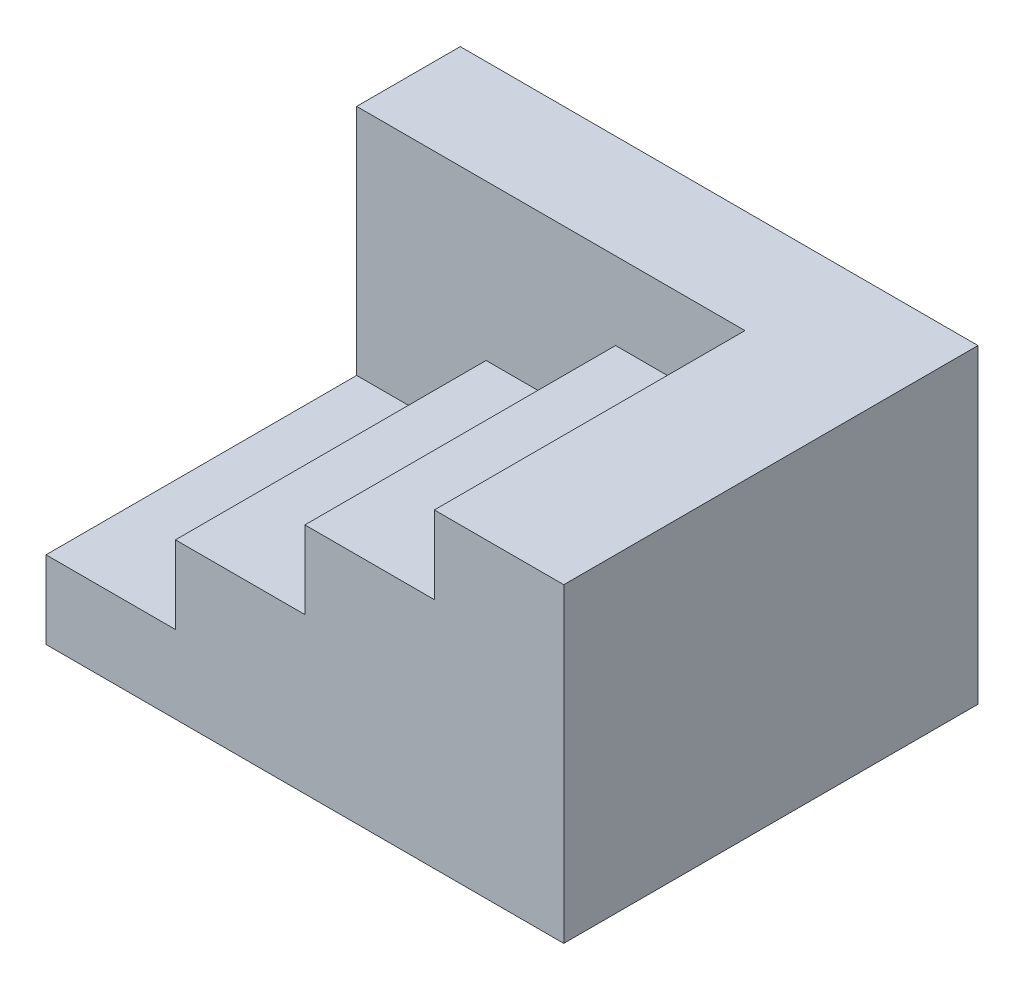
SolidWorks part; units mm, degrees
ref_plane "Front Plane" through (0, 0, 0) normal (0, 0, 1) x (1, 0, 0)
ref_plane "Top Plane" through (0, 0, 0) normal (0, 1, 0) x (1, 0, 0)
ref_plane "Right Plane" through (0, 0, 0) normal (1, 0, 0) x (0, 0, -1)
sketch "Sketch1" plane through (0, 0, 0) normal (0, 1, 0) x (1, 0, 0)
  line L1 (0, 0) -> (100, 0)
  line L2 (0, 0) -> (0, 80)
  line L3 (0, 80) -> (100, 80)
  line L4 (100, 0) -> (100, 80)
  dimension "D1" = 100
  dimension "D2" = 80
extrude "Boss-Extrude1" add sketch "Sketch1" along normal blind 60
sketch "Sketch3" plane through (0, 0, 0) normal (0, 0, 1) x (1, 0, 0)
  line L0 (0, 60) -> (75, 60)
  line L1 (0, 60) -> (100, 60) construction
  line L2 (75, 60) -> (75, 45)
  line L3 (75, 45) -> (50, 45)
  line L4 (50, 45) -> (50, 30)
  line L5 (50, 30) -> (25, 30)
  line L6 (25, 30) -> (25, 15)
  line L7 (25, 15) -> (0, 15)
  line L8 (0, 60) -> (0, 0) construction
  line L9 (0, 15) -> (0, 60)
  dimension "D1" = 15
  dimension "D2" = 25
extrude "Cut-Extrude1" cut sketch "Sketch3" against normal blind 60
